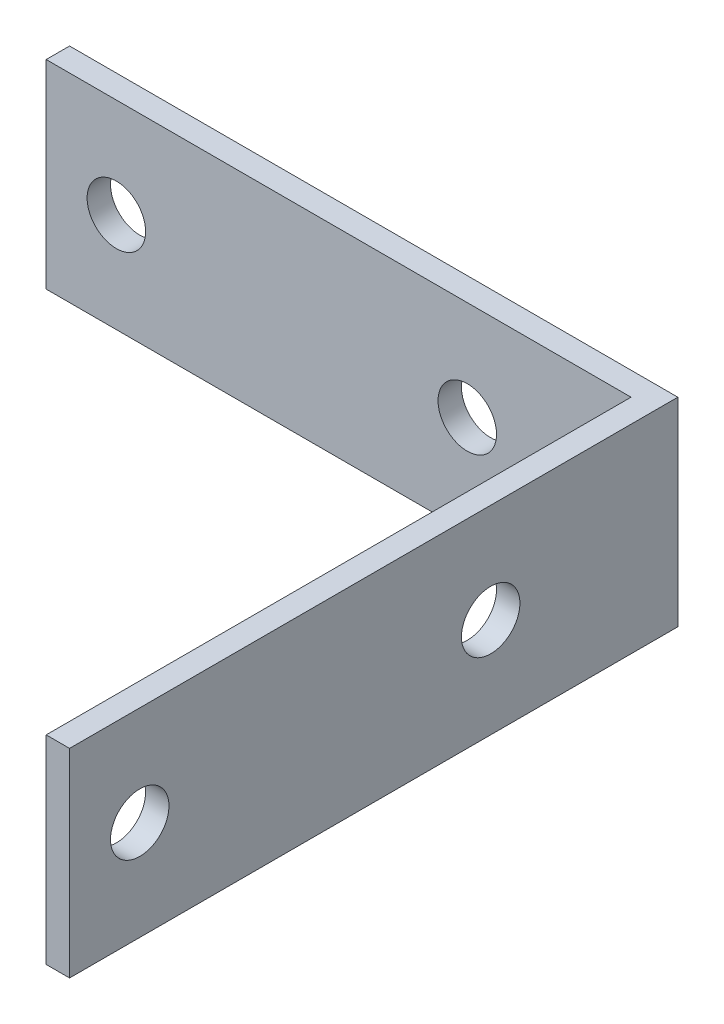
SolidWorks part; units mm, degrees
ref_plane "Plan de face" through (0, 0, 0) normal (0, 0, 1) x (1, 0, 0)
ref_plane "Plan de dessus" through (0, 0, 0) normal (0, 1, 0) x (1, 0, 0)
ref_plane "Plan de droite" through (0, 0, 0) normal (1, 0, 0) x (0, 0, -1)
sketch "Esquisse1" plane through (0, 0, 0) normal (0, 0, 1) x (1, 0, 0)
  line L1 (-26, 8.5) -> (26, 8.5)
  line L2 (-26, 8.5) -> (-26, -8.5)
  line L3 (-26, -8.5) -> (26, -8.5)
  line L4 (26, 8.5) -> (26, -8.5)
  line L5 (-26, 8.5) -> (26, -8.5) construction
  line L6 (-26, -8.5) -> (26, 8.5) construction
  point P0 (0, 0)
  dimension "D1" = 52
  dimension "D2" = 17
extrude "Boss.-Extru.1" add sketch "Esquisse1" along normal blind 2
sketch "Esquisse2" plane through (0, 0, 2) normal (0, 0, 1) x (1, 0, 0)
  line L0 (-26, -8.5) -> (26, -8.5) construction
  line L1 (26, 8.5) -> (24, 8.5)
  line L2 (26, 8.5) -> (26, -8.5)
  line L3 (26, -8.5) -> (24, -8.5)
  line L4 (24, 8.5) -> (24, -8.5)
  dimension "D1" = 2
extrude "Boss.-Extru.2" add sketch "Esquisse2" along normal blind 50
sketch "Esquisse3" plane through (0, 0, 2) normal (0, 0, 1) x (1, 0, 0)
  line L0 (-26, 8.5) -> (-26, -8.5) construction
  line L1 (24, 8.5) -> (-26, 8.5) construction
  circle A0 centre (-20, 0) radius 2.5
  circle A1 centre (10, 0) radius 2.5
  point P6 (-26, 0)
  dimension "D2" = 5
  dimension "D3" = 8.5
  dimension "D5" = 5
  dimension "D1" = 6
  dimension "D4" = 30
  dimension "D6" = 8.5
extrude "Enlèv. mat.-Extru.1" cut sketch "Esquisse3" against normal blind 50
sketch "Esquisse4" plane through (24, 0, 0) normal (-1, 0, 0) x (0, 0, 1)
  line L0 (52, 8.5) -> (52, -8.5) construction
  line L1 (52, 8.5) -> (2, 8.5) construction
  circle A0 centre (46, 0) radius 2.5
  circle A1 centre (16, 0) radius 2.5
  point P6 (52, 0)
  dimension "D1" = 5
  dimension "D2" = 5
  dimension "D3" = 6
  dimension "D4" = 30
  dimension "D5" = 8.5
  dimension "D6" = 8.5
extrude "Enlèv. mat.-Extru.2" cut sketch "Esquisse4" against normal blind 50
